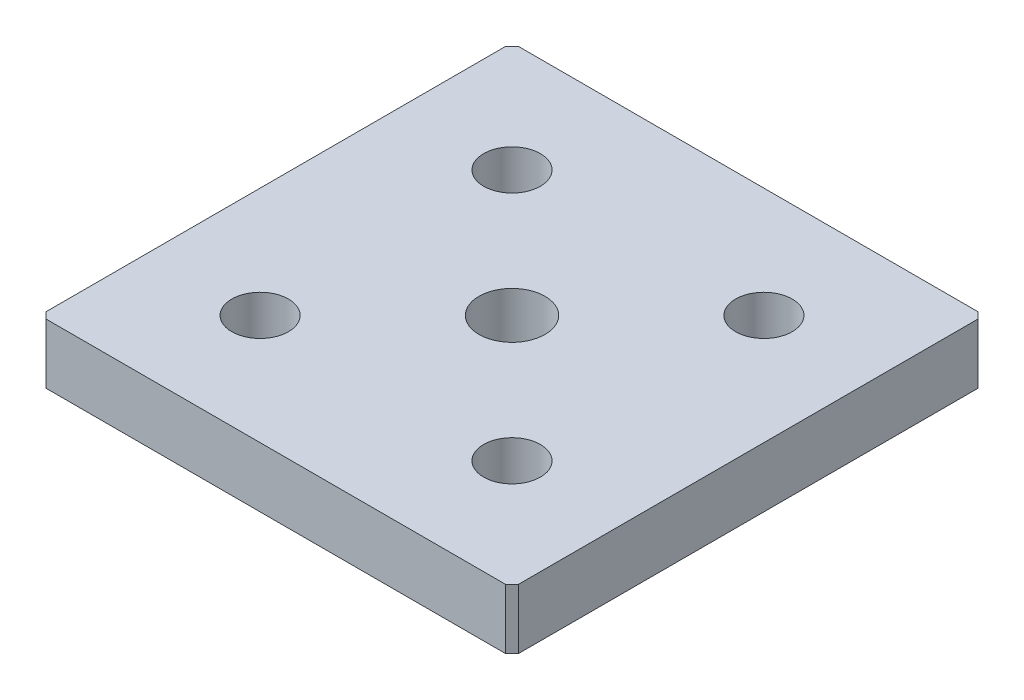
SolidWorks part; units mm, degrees
material "6061-T6 (SS)"
ref_plane "Front Plane" through (0, 0, 0) normal (0, 0, 1) x (1, 0, 0)
ref_plane "Top Plane" through (0, 0, 0) normal (0, 1, 0) x (1, 0, 0)
ref_plane "Right Plane" through (0, 0, 0) normal (1, 0, 0) x (0, 0, -1)
sketch "Sketch1" plane through (0, 0, 0) normal (0, 1, 0) x (1, 0, 0)
  line L1 (-37.5, 37.5) -> (37.5, 37.5)
  line L2 (-37.5, 37.5) -> (-37.5, -37.5)
  line L3 (-37.5, -37.5) -> (37.5, -37.5)
  line L4 (37.5, 37.5) -> (37.5, -37.5)
  line L5 (-37.5, 37.5) -> (37.5, -37.5) construction
  line L6 (-37.5, -37.5) -> (37.5, 37.5) construction
  point P0 (0, 0)
  dimension "D1" = 75
  dimension "D2" = 75
extrude "Boss-Extrude1" add sketch "Sketch1" along normal mid plane 9.525
hole_wizard "M8 Clearance Hole1" positions "Sketch2" profile "Sketch3" hole size "M8" standard "ANSI Metric" end condition through all
sketch "Sketch2" plane through (0, 4.7625, 0) normal (0, 1, 0) x (1, 0, 0)
  line L0 (20, 20) -> (-20, 20)
  line L2 (20, 20) -> (20, -20)
  line L3 (20, -20) -> (-20, -20)
  line L4 (-20, -20) -> (-20, 20)
  line L6 (-20, 20) -> (20, -20)
  point P0 (-20, 20)
  point P2 (20, 20)
  point P22 (-20, -20)
  point P25 (20, -20)
  dimension "D1" = 40
sketch "Sketch3" plane through (-20, 4.7625, -20) normal (1, 0, 0) x (0, 0, 1)
  line L0 (0, 0) -> (0, 9.525)
  line L1 (0, 9.525) -> (4.5, 9.525)
  line L2 (4.5, 9.525) -> (4.5, 0)
  line L5 (4.5, 0) -> (0, 0)
  line L11 (0, -6.35) -> (0, 107.95) construction
  dimension "Thru Hole Dia." = 9
  dimension "Thru Hole Depth" = 9.525
hole_wizard "M12x1.5 Tapped Hole1" positions "Sketch4" profile "Sketch5" tap size "M12x1.5" standard "ANSI Metric" end condition through all
sketch "Sketch4" plane through (0, 4.7625, 0) normal (0, 1, 0) x (1, 0, 0)
  point P0 (0, 0)
sketch "Sketch5" plane through (0, 4.7625, 0) normal (1, 0, 0) x (0, 0, 1)
  line L0 (0, 0) -> (0, 9.525)
  line L1 (0, 9.525) -> (5.25, 9.525)
  line L2 (5.25, 9.525) -> (5.25, 0)
  line L5 (5.25, 0) -> (0, 0)
  line L11 (0, -6.35) -> (0, 107.95) construction
  dimension "Thru Tap Drill Dia." = 10.5
  dimension "Thru Tap Drill Depth" = 9.525
cosmetic thread "Hole Thread1" parameters "D2"=12
chamfer "Chamfer1" distance 1 angle 45 4 edges at (37.5, 0, -37.5) (37.5, 0, 37.5) (-37.5, 0, 37.5) (-37.5, 0, -37.5)
